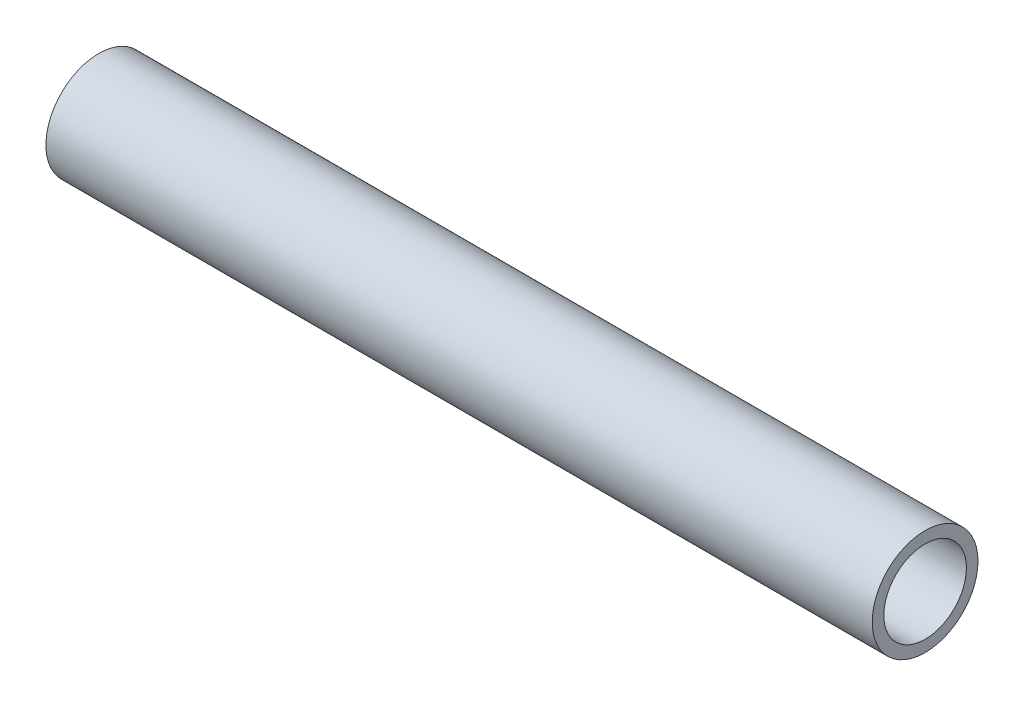
SolidWorks part; units mm, degrees
material "STD Carbon Fiber"
ref_plane "Front Plane" through (0, 0, 0) normal (0, 0, 1) x (1, 0, 0)
ref_plane "Top Plane" through (0, 0, 0) normal (0, 1, 0) x (1, 0, 0)
ref_plane "Right Plane" through (0, 0, 0) normal (1, 0, 0) x (0, 0, -1)
other "Carbon Fiber"
sketch "Sketch1" plane through (0, 0, 0) normal (1, 0, 0) x (0, 0, -1)
  circle A0 centre (0, 0) radius 3.175
  circle A1 centre (0, 0) radius 4.064
  dimension "D2" = 6.35
  dimension "D1" = 0.889
extrude "Boss-Extrude1" add sketch "Sketch1" along normal blind 63.5
